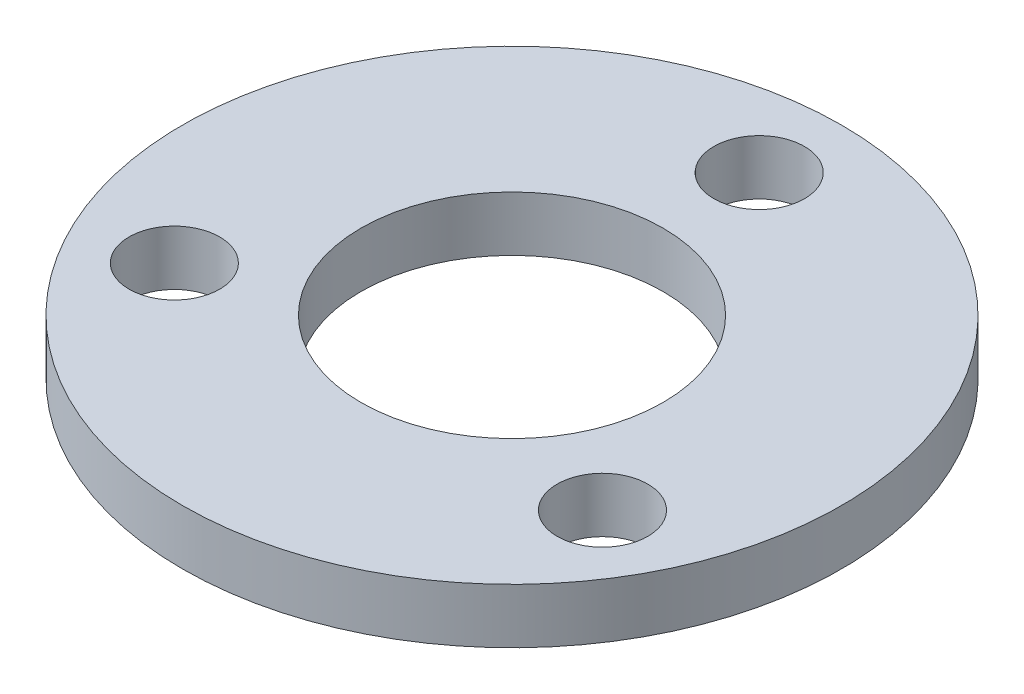
SolidWorks part; units mm, degrees
ref_plane "Спереди" through (0, 0, 0) normal (0, 0, 1) x (1, 0, 0)
ref_plane "Сверху" through (0, 0, 0) normal (0, 1, 0) x (1, 0, 0)
ref_plane "Справа" through (0, 0, 0) normal (1, 0, 0) x (0, 0, -1)
sketch "Эскиз1" plane through (0, 0, 0) normal (0, 1, 0) x (1, 0, 0)
  line L0 (0, 0) -> (0, 21.901) construction
  line L1 (0, 0) -> (-18.0489, -10.4205) construction
  line L2 (0, 0) -> (18.1135, -10.4578) construction
  circle A0 centre (0, 0) radius 12
  circle A1 centre (0, 0) radius 9 construction
  circle A2 centre (0, 9) radius 1.65
  circle A3 centre (0, 0) radius 10.65 construction
  circle A4 centre (7.7942, -4.5) radius 1.65
  circle A5 centre (-7.7942, -4.5) radius 1.65
  circle A7 centre (0, 0) radius 5.5
  dimension "D1" = 24
  dimension "D2" = 21.3
  dimension "D3" = 18
  dimension "D4" = 11
  dimension "D6" = 120
  dimension "D5" = 120
extrude "Бобышка-Вытянуть1" add sketch "Эскиз1" along normal blind 2
